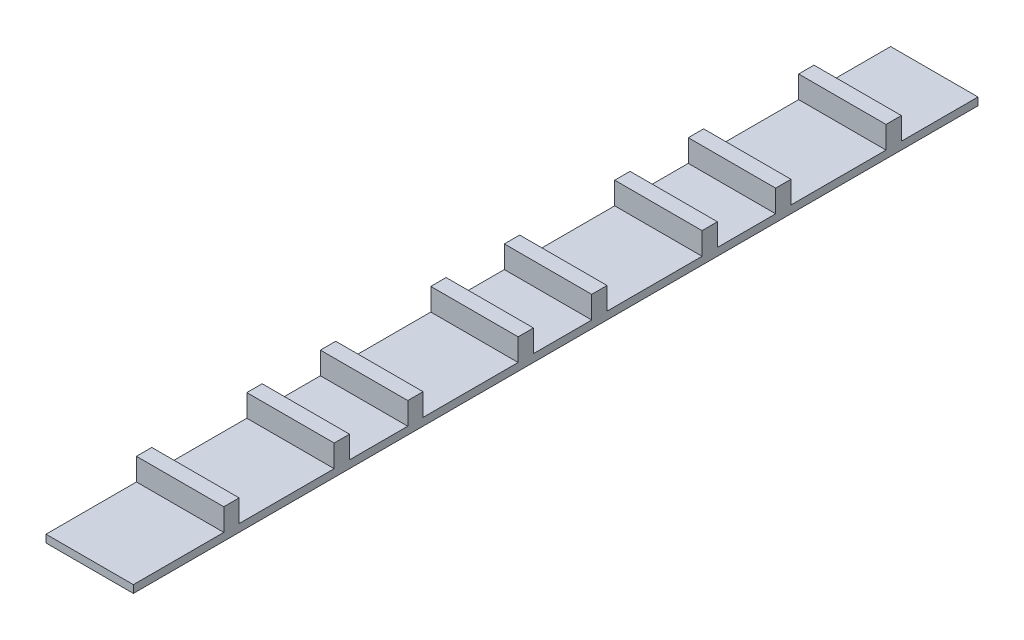
SolidWorks part; units mm, degrees
ref_plane "Front Plane" through (0, 0, 0) normal (0, 0, 1) x (1, 0, 0)
ref_plane "Top Plane" through (0, 0, 0) normal (0, 1, 0) x (1, 0, 0)
ref_plane "Right Plane" through (0, 0, 0) normal (1, 0, 0) x (0, 0, -1)
sketch "Sketch2" plane through (0, 0, 0) normal (0, 0, 1) x (1, 0, 0)
  line L1 (0, 0) -> (5.7, 0)
  line L2 (0, 0) -> (0, 0.5)
  line L3 (0, 0.5) -> (5.7, 0.5)
  line L4 (5.7, 0) -> (5.7, 0.5)
  dimension "D1" = 0.5
  dimension "D2" = 5.7
extrude "Boss-Extrude1" add sketch "Sketch2" along normal blind 55.1
sketch "Sketch3" plane through (0, 0.5, 0) normal (0, 1, 0) x (1, 0, 0)
  line L0 (0, -55.1) -> (0, 0) construction
  line L1 (0, -5) -> (5.7, -5)
  line L2 (0, -5) -> (0, -6)
  line L3 (0, -6) -> (5.7, -6)
  line L4 (5.7, -5) -> (5.7, -6)
  line L5 (5.7, -55.1) -> (5.7, 0) construction
  line L6 (5.7, 0) -> (0, 0) construction
  line L8 (0, -12.2) -> (5.7, -12.2)
  line L9 (0, -12.2) -> (0, -13.2)
  line L10 (0, -13.2) -> (5.7, -13.2)
  line L11 (5.7, -12.2) -> (5.7, -13.2)
  dimension "D1" = 5
  dimension "D2" = 1
  dimension "D3" = 6.2
extrude "Boss-Extrude2" add sketch "Sketch3" along normal blind 1.45
pattern_linear "LPattern1" count 4 spacing 12 along (0, 0, 1) of "Boss-Extrude2"
